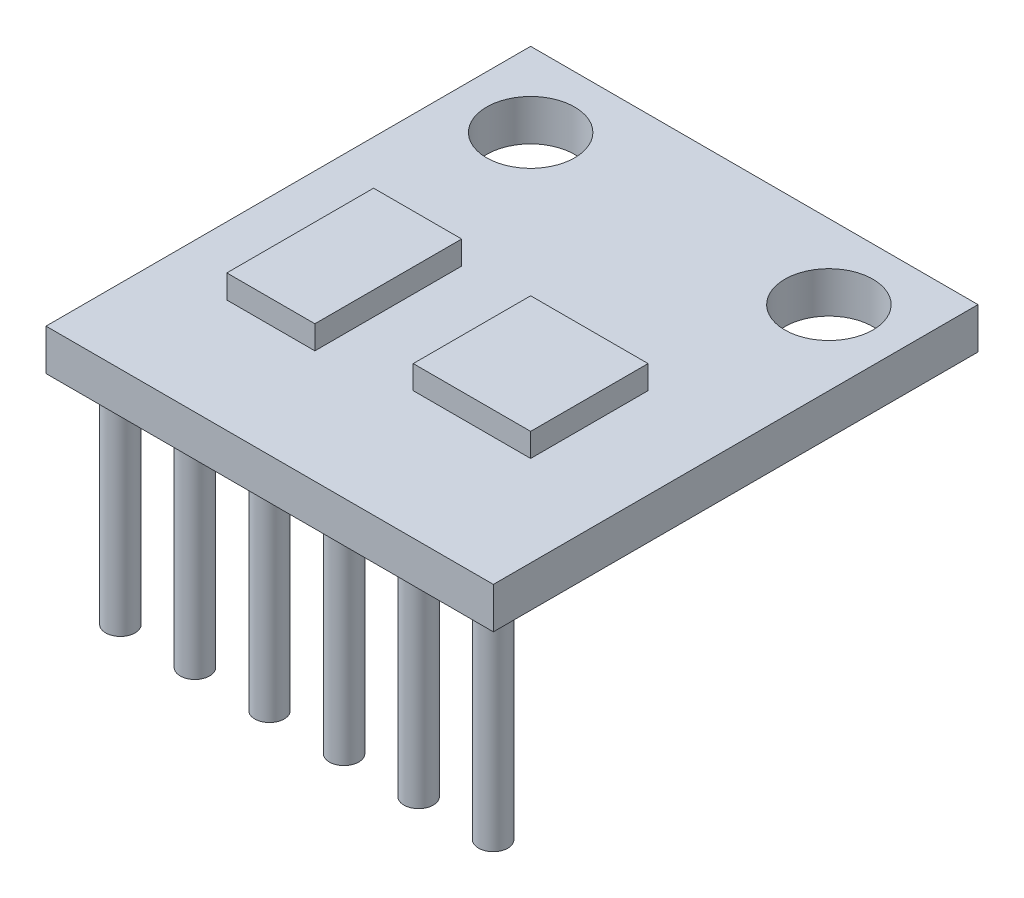
SolidWorks part; units mm, degrees
ref_plane "Plan de face" through (0, 0, 0) normal (0, 0, 1) x (1, 0, 0)
ref_plane "Plan de dessus" through (0, 0, 0) normal (0, 1, 0) x (1, 0, 0)
ref_plane "Plan de droite" through (0, 0, 0) normal (1, 0, 0) x (0, 0, -1)
sketch "Esquisse1" plane through (0, 0, 0) normal (0, 1, 0) x (1, 0, 0)
  line L1 (7.6104, -5.3282) -> (-7.6296, -5.3282)
  line L2 (7.6104, -5.3282) -> (7.6104, 11.1818)
  line L3 (7.6104, 11.1818) -> (-7.6296, 11.1818)
  line L4 (-7.6296, -5.3282) -> (-7.6296, 11.1818)
  circle A0 centre (-5.0896, 8.6418) radius 1.5
  circle A1 centre (5.0704, 8.6418) radius 1.5
  dimension "D15" = 3
  dimension "D16" = 3
  dimension "D1" = 16.51
  dimension "D2" = 15.24
  dimension "D11" = 2.54
  dimension "D12" = 2.54
  dimension "D13" = 2.54
  dimension "D14" = 2.54
extrude "PCB" add sketch "Esquisse1" along normal blind 1.4
sketch "Esquisse2" plane through (0, 1.4, 0) normal (0, 1, 0) x (1, 0, 0)
  line L0 (-7.6296, -5.3282) -> (7.6104, -5.3282) construction
  line L1 (-2.3196, -1.4782) -> (-5.3196, -1.4782)
  line L2 (-2.3196, -1.4782) -> (-2.3196, 3.5218)
  line L3 (-2.3196, 3.5218) -> (-5.3196, 3.5218)
  line L4 (-5.3196, -1.4782) -> (-5.3196, 3.5218)
  line L5 (-2.3196, -1.4782) -> (-5.3196, 3.5218) construction
  line L6 (-2.3196, 3.5218) -> (-5.3196, -1.4782) construction
  line L7 (-7.6296, 11.1818) -> (-7.6296, -5.3282) construction
  point P0 (-3.8196, 1.0218)
  dimension "D1" = 6.35
  dimension "D2" = 3.81
  dimension "D3" = 3
  dimension "D4" = 5
extrude "ADXL345" add sketch "Esquisse2" along normal blind 0.8
sketch "Esquisse3" plane through (0, 1.4, 0) normal (0, 1, 0) x (1, 0, 0)
  line L0 (-7.6296, -5.3282) -> (7.6104, -5.3282) construction
  line L1 (4.5304, -0.9782) -> (0.5304, -0.9782)
  line L2 (4.5304, -0.9782) -> (4.5304, 3.0218)
  line L3 (4.5304, 3.0218) -> (0.5304, 3.0218)
  line L4 (0.5304, -0.9782) -> (0.5304, 3.0218)
  line L5 (4.5304, -0.9782) -> (0.5304, 3.0218) construction
  line L6 (4.5304, 3.0218) -> (0.5304, -0.9782) construction
  line L7 (-7.6296, 11.1818) -> (-7.6296, -5.3282) construction
  point P0 (2.5304, 1.0218)
  dimension "D1" = 6.35
  dimension "D2" = 4
  dimension "D3" = 4
  dimension "D4" = 10.16
extrude "ITG-3200" add sketch "Esquisse3" along normal blind 0.8
sketch "Esquisse6" plane through (0, 0, 0) normal (0, -1, 0) x (1, 0, 0)
  line L0 (-7.6296, -11.1818) -> (-7.6296, 5.3282) construction
  circle A0 centre (-6.3596, 4.0643) radius 0.5
  circle A1 centre (-3.8196, 4.0643) radius 0.5
  circle A2 centre (-1.2796, 4.0643) radius 0.5
  circle A3 centre (1.2604, 4.0643) radius 0.5
  circle A4 centre (3.8004, 4.0643) radius 0.5
  circle A5 centre (6.3404, 4.0643) radius 0.5
  dimension "D2" = 1
  dimension "D1" = 1.27
  dimension "D3" = 6
extrude "Boss.-Extru.9" add sketch "Esquisse6" along normal blind 7.4
ref_point "Point1"
ref_point "Point2"
